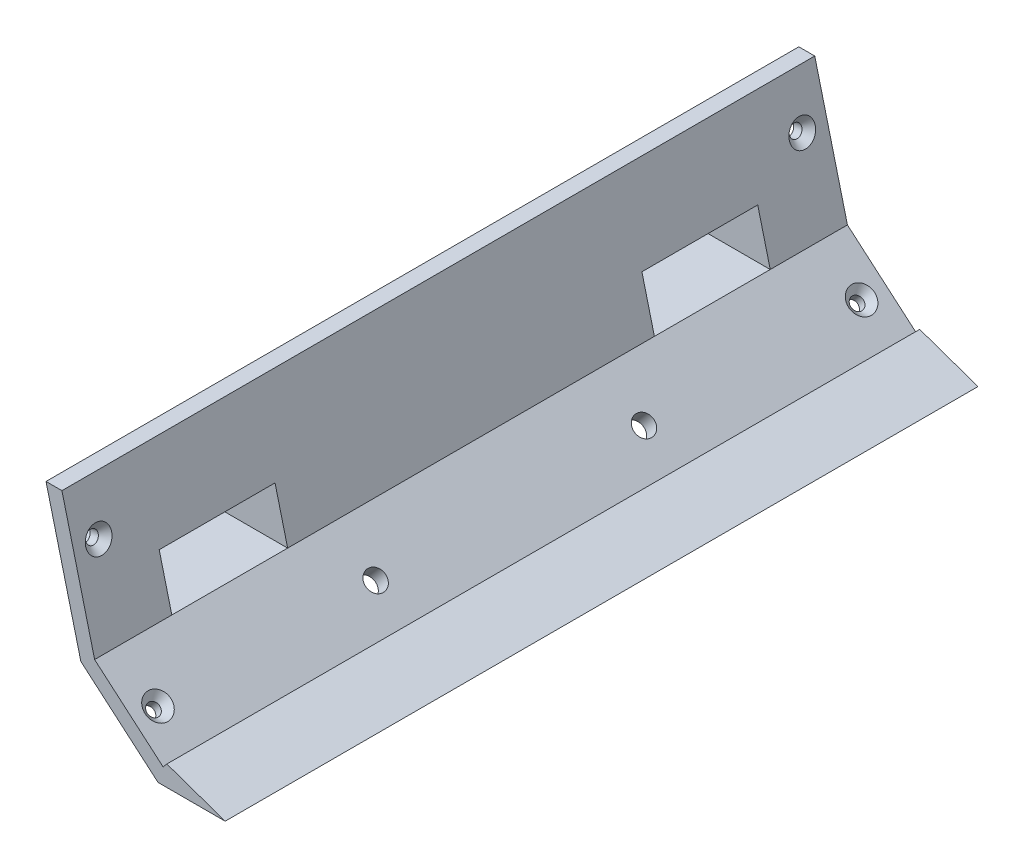
SolidWorks part; units mm, degrees
ref_plane "Alzado" through (0, 0, 0) normal (0, 0, 1) x (1, 0, 0)
ref_plane "Planta" through (0, 0, 0) normal (0, 1, 0) x (1, 0, 0)
ref_plane "Vista lateral" through (0, 0, 0) normal (1, 0, 0) x (0, 0, -1)
sketch "Croquis1" plane through (0, 0, 0) normal (0, 0, 1) x (1, 0, 0)
  line L0 (77.0085, 1.6467) -> (77.9847, 2.7856)
  line L1 (77.9847, 2.7856) -> (93.0864, -2.5)
  line L2 (93.0864, -2.5) -> (75.7, -2.5)
  line L3 (75.7, -2.5) -> (55.7, 14.6421)
  line L4 (55.7, 14.6421) -> (46.6759, 50.5119)
  line L5 (59.2688, 16.8514) -> (77.0085, 1.6467)
  line L8 (59.2688, 16.8514) -> (50.8006, 50.5119)
  line L9 (46.6759, 50.5119) -> (50.8006, 50.5119)
  dimension "D1" = 50.8006
  dimension "D3" = 59.2688
extrude "Saliente-Extruir1" add sketch "Croquis1" against normal up to vertex (195 mm away)
sketch "Croquis2" plane through (55.8489, 14.0503, 0) normal (-0.9698, -0.244, 0) x (0, 0, 1)
  circle A0 centre (-188.625, 23.7274) radius 1.625
  circle A1 centre (-6.375, 23.7274) radius 1.625
  dimension "D1" = 3.25
extrude "Cortar-Extruir1" cut sketch "Croquis2" against normal up to vertex (4 mm away)
sketch "Croquis3" plane through (30.8242, 35.9632, 0) normal (-0.6508, -0.7593, 0) x (0.7593, -0.6508, 0)
  circle A0 centre (47.2622, -188.625) radius 1.625
  circle A1 centre (47.2622, -6.375) radius 1.625
  dimension "D1" = 3.25
extrude "Cortar-Extruir2" cut sketch "Croquis3" against normal up to vertex (4 mm away)
sketch "Croquis4" plane through (33.4273, 39.0003, 0) normal (0.6508, 0.7593, 0) x (0.7593, -0.6508, 0)
  circle A0 centre (47.2622, 6.375) radius 3.36
  circle A1 centre (47.2622, 188.625) radius 3.36
  dimension "D1" = 6.7199
  dimension "D2" = 6.7199
extrude "Cortar-Extruir3" cut sketch "Croquis4" against normal blind 1.8 draft 44
sketch "Croquis5" plane through (59.728, 15.0262, 0) normal (0.9698, 0.244, 0) x (0, 0, -1)
  circle A0 centre (6.375, 23.7274) radius 3.36
  circle A1 centre (188.625, 23.7274) radius 3.36
  dimension "D1" = 6.7199
  dimension "D2" = 6.7199
extrude "Cortar-Extruir4" cut sketch "Croquis5" against normal blind 1.8 draft 44
ref_plane "Plano1" through (59.2688, 16.8514, -195) normal (0, 0, 1) x (1, 0, 0)
sketch "Croquis7" plane through (0, 0, -195) normal (0, 0, -1) x (-1, 0, 0)
  line L0 (-59.2688, 16.8514) -> (-55.1442, 16.8514) construction
  line L1 (-46.6759, 50.5119) -> (-55.7, 14.6421) construction
  line L3 (-59.2688, 16.8514) -> (-56.0313, 29.7201)
  line L4 (-59.2688, 16.8514) -> (-55.1442, 16.8514)
  line L6 (-56.0313, 29.7201) -> (-51.9067, 29.7201)
  line L8 (-59.2688, 16.8514) -> (-50.8006, 50.5119) construction
  line L9 (-55.1442, 16.8514) -> (-51.9067, 29.7201)
  dimension "D1" = 37.0551
extrude "Cortar-Extruir5" cut sketch "Croquis7" against normal blind 50
sketch "Croquis9" plane through (0, 0, 0) normal (0, 0, 1) x (1, 0, 0)
  line L0 (59.2688, 16.8514) -> (55.1442, 16.8514)
  line L1 (51.8737, 29.8514) -> (55.1442, 16.8514)
  line L2 (55.9983, 29.8514) -> (59.2688, 16.8514)
  line L3 (46.6759, 50.5119) -> (55.7, 14.6421) construction
  line L4 (51.8737, 29.8514) -> (55.9983, 29.8514)
  line L5 (59.2688, 16.8514) -> (50.8006, 50.5119) construction
  dimension "D1" = 21.0102
extrude "Cortar-Extruir6" cut sketch "Croquis9" against normal blind 50
sketch "Croquis10" plane through (0, 16.8514, 0) normal (0, 1, 0) x (1, 0, 0)
  line L0 (59.2688, 50) -> (39.8253, 50)
  line L1 (59.2688, 50) -> (59.2688, 0) construction
  line L2 (59.2688, 50) -> (59.2688, 20)
  line L3 (55.1442, 0) -> (59.2688, 0) construction
  line L4 (59.2688, 20) -> (39.8253, 20)
  line L6 (39.8253, 20) -> (39.8253, 50)
  line L7 (59.2688, 145) -> (39.8253, 145)
  line L13 (59.2688, 145) -> (59.2688, 175)
  line L15 (59.2688, 175) -> (39.8253, 175)
  line L16 (39.8253, 175) -> (39.8253, 145)
  dimension "D1" = 19.4435
  dimension "D2" = 20
  dimension "D3" = 50
  dimension "D4" = 145
extrude "Saliente-Extruir2" add sketch "Croquis10" against normal up to vertex (2.2094 mm away)
sketch "Croquis11" plane through (0, 29.7201, 0) normal (0, -1, 0) x (1, 0, 0)
  line L0 (56.0313, -145) -> (56.0313, -195) construction
  line L2 (56.0313, -145) -> (56.0313, -175)
  line L6 (56.0313, -145) -> (39.8253, -145)
  line L7 (39.8253, -145) -> (39.8253, -155.7)
  line L8 (39.8253, -175) -> (56.0313, -175)
  line L15 (39.8253, -155.7) -> (41.8753, -155.7)
  line L16 (37.1253, -155.7) -> (49.7253, -155.7) construction
  line L17 (41.8753, -155.7) -> (41.8753, -164.3)
  line L18 (41.8753, -164.3) -> (39.8253, -164.3)
  line L19 (39.8253, -164.3) -> (39.8253, -175)
  dimension "D1" = 14.156
extrude "Saliente-Extruir3" add sketch "Croquis11" against normal blind 2
sketch "Croquis12" plane through (0, 29.8514, 0) normal (0, -1, 0) x (1, 0, 0)
  line L2 (55.9983, -50) -> (55.9983, -20)
  line L6 (55.9983, -20) -> (39.8253, -20)
  line L7 (39.8253, -20) -> (39.8253, -30.7)
  line L8 (39.8253, -50) -> (55.9983, -50)
  line L9 (51.8737, -50) -> (51.8737, 0) construction
  line L15 (39.8253, -39.3) -> (41.8753, -39.3)
  line L16 (41.8753, -39.3) -> (41.8753, -30.7)
  line L17 (37.1253, -30.7) -> (49.7253, -30.7) construction
  line L18 (41.8753, -30.7) -> (39.8253, -30.7)
  line L19 (39.8253, -39.3) -> (39.8253, -50)
  dimension "D1" = 4.1246
  dimension "D2" = 9.9984
extrude "Saliente-Extruir4" add sketch "Croquis12" against normal blind 2
sketch "Croquis14" plane through (39.8253, 0, 0) normal (-1, 0, 0) x (0, 0, 1)
  line L0 (-137.75, 26.5514) -> (-137.75, 19.011)
  line L1 (-12.75, 26.5514) -> (-20, 31.8514)
  line L2 (-20, 31.8514) -> (-20, 14.6421)
  line L3 (-50, 16.8514) -> (-20, 16.8514) construction
  line L4 (-145, 31.7201) -> (-145, 14.6421)
  line L6 (-145, 14.6421) -> (-137.75, 19.011)
  line L7 (-12.75, 11.8804) -> (-12.75, 46.5119) construction
  line L8 (-12.75, 26.5514) -> (-12.75, 19.0514)
  line L9 (-12.75, 19.0514) -> (-20, 14.6421)
  line L10 (-57.25, 19.0514) -> (-57.25, 26.5514)
  line L11 (-57.25, 26.5514) -> (-50, 31.8514)
  line L12 (-50, 31.8514) -> (-50, 14.6421)
  line L13 (-50, 14.6421) -> (-57.25, 19.0514)
  line L15 (-137.75, 26.5514) -> (-145, 31.7201)
  line L16 (-182.25, 22.8014) -> (-182.25, 19.0514) construction
  line L17 (-182.25, 46.5119) -> (-182.25, 11.8804) construction
  line L18 (-182.25, 19.0514) -> (-175, 14.6421)
  line L19 (-175, 14.6421) -> (-175, 31.7201)
  line L20 (-175, 31.7201) -> (-182.25, 26.5514)
  line L21 (-182.25, 26.5514) -> (-182.25, 19.0514)
  arc A3 (-178.5, 26.5514) -> (-178.5, 19.0514) centre (-178.5, 22.8014) ccw construction
  dimension "D1" = 2.1595
  dimension "D2" = 7.5
  dimension "D3" = 7.5405
  dimension "D4" = 7.5
  dimension "D5" = 7.5
  dimension "D6" = 8.9807
  dimension "D7" = 8.4856
extrude "Saliente-Extruir5" add sketch "Croquis14" against normal up to vertex (16.206 mm away)
sketch "Croquis15" plane through (39.8253, 0, 0) normal (-1, 0, 0) x (0, 0, 1)
  line L0 (-182.25, 26.5514) -> (-181.0286, 27.4222)
  line L1 (-175, 31.7201) -> (-182.25, 26.5514) construction
  line L2 (-181.0286, 27.4222) -> (-181.0286, 18.3086)
  line L3 (-182.25, 19.0514) -> (-175, 14.6421) construction
  line L4 (-181.0286, 18.3086) -> (-182.25, 19.0514)
  line L5 (-182.25, 19.0514) -> (-182.25, 26.5514)
  line L6 (-12.75, 26.5514) -> (-13.9609, 27.4367)
  line L7 (-12.75, 26.5514) -> (-20, 31.8514) construction
  line L8 (-13.9609, 27.4367) -> (-13.9609, 18.315)
  line L9 (-20, 14.6421) -> (-12.75, 19.0514) construction
  line L10 (-13.9609, 18.315) -> (-12.75, 19.0514)
  line L11 (-12.75, 19.0514) -> (-12.75, 26.5514)
  dimension "D1" = 161.0391
extrude "Cortar-Extruir8" cut sketch "Croquis15" against normal up to vertex
sketch "Croquis16" plane through (39.8253, 0, 0) normal (-1, 0, 0) x (0, 0, 1)
  circle A0 centre (-53.5, 22.8014) radius 1.6
  circle A1 centre (-16.5, 22.8014) radius 1.6
  circle A2 centre (-178.5, 22.8014) radius 1.6
  circle A3 centre (-141.5, 22.8014) radius 1.6
  dimension "D1" = 3.2
extrude "Cortar-Extruir9" cut sketch "Croquis16" against normal blind 4
sketch "Croquis17" plane through (0, 0, 0) normal (0, 0, 1) x (1, 0, 0)
  line L0 (51.8737, 29.8514) -> (55.9983, 29.8514)
  line L1 (55.9983, 29.8514) -> (59.2688, 16.8514)
  line L2 (59.2688, 16.8514) -> (55.1442, 16.8514)
  line L3 (55.1442, 16.8514) -> (51.8737, 29.8514)
extrude "Saliente-Extruir6" add sketch "Croquis17" against normal up to vertex (20 mm away) up to point (56.0313, 31.8514, -20)
sketch "Croquis18" plane through (0, 0, -195) normal (0, 0, -1) x (-1, 0, 0)
  line L0 (-59.2688, 16.8514) -> (-55.1442, 16.8514)
  line L1 (-55.1442, 16.8514) -> (-51.9067, 29.7201)
  line L2 (-51.9067, 29.7201) -> (-56.0313, 29.7201)
  line L3 (-56.0313, 29.7201) -> (-59.2688, 16.8514)
extrude "Saliente-Extruir7" add sketch "Croquis18" against normal up to vertex
sketch "Croquis19" plane through (33.4273, 39.0003, 0) normal (0.6508, 0.7593, 0) x (0.7593, -0.6508, 0)
  line L0 (34.0346, 50) -> (34.0346, 62.75) construction
  line L1 (34.0346, 145) -> (34.0346, 50) construction
  line L2 (34.0346, 145) -> (34.0346, 132.25) construction
  line L4 (47.2622, 6.375) -> (47.2622, 62.75) construction
  line L5 (34.0346, 132.25) -> (47.2622, 132.25) construction
  line L6 (57.3987, 195) -> (57.3987, 0) construction
  circle A0 centre (47.2622, 62.75) radius 2.625
  circle A1 centre (47.2622, 132.25) radius 2.625
  dimension "D1" = 5.25
  dimension "D2" = 62.75
extrude "Cortar-Extruir10" cut sketch "Croquis19" against normal up to vertex (4 mm away)
sketch "Croquis20" plane through (0, 0, -195) normal (0, 0, -1) x (-1, 0, 0)
  line L0 (-56.0313, 29.7201) -> (-56.0313, 31.8514)
  line L1 (-56.0313, 31.8514) -> (-55.4951, 31.8514)
  line L2 (-55.4951, 31.8514) -> (-56.0313, 29.7201)
extrude "Cortar-Extruir11" cut sketch "Croquis20" against normal up to vertex
